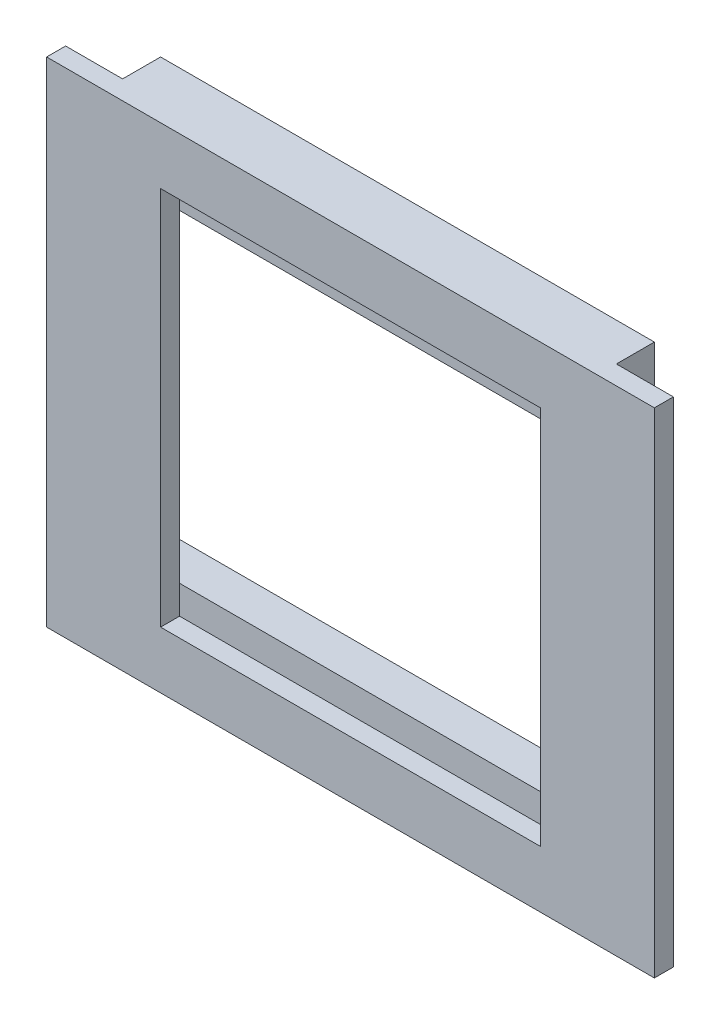
SolidWorks part; units mm, degrees
ref_plane "Спереди" through (0, 0, 0) normal (0, 0, 1) x (1, 0, 0)
ref_plane "Сверху" through (0, 0, 0) normal (0, 1, 0) x (1, 0, 0)
ref_plane "Справа" through (0, 0, 0) normal (1, 0, 0) x (0, 0, -1)
sketch "Sketch1" plane through (0, 0, 0) normal (0, 0, 1) x (1, 0, 0)
  line L1 (-74.5188, 51.1297) -> (55.4812, 51.1297)
  line L2 (-74.5188, 51.1297) -> (-74.5188, -78.8703)
  line L3 (-74.5188, -78.8703) -> (55.4812, -78.8703)
  line L4 (55.4812, 51.1297) -> (55.4812, -78.8703)
  dimension "D1" = 130
  dimension "D2" = 130
extrude "Boss-Extrude1" add sketch "Sketch1" along normal blind 15
sketch "Sketch2" plane through (0, 0, 15) normal (0, 0, 1) x (1, 0, 0)
  line L0 (-74.5188, -78.8703) -> (55.4812, -78.8703) construction
  line L1 (55.4812, 51.1297) -> (70.4812, 51.1297)
  line L2 (55.4812, 51.1297) -> (55.4812, -78.8703)
  line L3 (55.4812, -78.8703) -> (70.4812, -78.8703)
  line L4 (70.4812, 51.1297) -> (70.4812, -78.8703)
  line L5 (-9.5188, 51.1297) -> (-9.5188, -78.8703) construction
  line L6 (55.4812, 51.1297) -> (-74.5188, 51.1297) construction
  line L7 (-74.5188, -78.8703) -> (-89.5188, -78.8703)
  line L8 (-89.5188, 51.1297) -> (-89.5188, -78.8703)
  line L9 (-74.5188, 51.1297) -> (-89.5188, 51.1297)
  line L10 (-74.5188, 51.1297) -> (-74.5188, -78.8703)
  dimension "D1" = 15
extrude "Boss-Extrude2" add sketch "Sketch2" against normal blind 5
sketch "Sketch3" plane through (0, 0, 15) normal (0, 0, 1) x (1, 0, 0)
  line L0 (-89.5188, 51.1297) -> (70.4812, -78.8703)
  line L1 (70.4812, 51.1297) -> (-89.5188, -78.8703)
  line L3 (-59.5188, -63.8703) -> (40.4812, -63.8703)
  line L4 (-59.5188, -63.8703) -> (-59.5188, 36.1297)
  line L5 (-59.5188, 36.1297) -> (40.4812, 36.1297)
  line L6 (40.4812, -63.8703) -> (40.4812, 36.1297)
  line L7 (-59.5188, -63.8703) -> (40.4812, 36.1297) construction
  line L8 (-59.5188, 36.1297) -> (40.4812, -63.8703) construction
  point P6 (-9.5188, -13.8703)
  dimension "D1" = 100
  dimension "D2" = 100
extrude "Cut-Extrude2" cut sketch "Sketch3" against normal blind 5 contours L4 L1 L0 | L1 L6 L5 L4 L0 | L3 L6 L0 L1 L4 | L0 L6 L1
sketch "Sketch5" plane through (0, 0, 10) normal (0, 0, 1) x (1, 0, 0)
  line L0 (-59.5188, -63.8703) -> (40.4812, 36.1297)
  line L1 (-59.5188, -63.8703) -> (40.4812, -63.8703) construction
  line L2 (-59.5188, -63.8703) -> (-59.5188, 36.1297) construction
  line L3 (40.4812, -63.8703) -> (-59.5188, 36.1297)
  line L5 (-47.5188, 28.6297) -> (28.4812, 28.6297)
  line L6 (-47.5188, 28.6297) -> (-47.5188, -56.3703)
  line L7 (-47.5188, -56.3703) -> (28.4812, -56.3703)
  line L8 (28.4812, 28.6297) -> (28.4812, -56.3703)
  line L9 (-47.5188, 28.6297) -> (28.4812, -56.3703) construction
  line L10 (-47.5188, -56.3703) -> (28.4812, 28.6297) construction
  point P12 (-9.5188, -13.8703)
  dimension "D1" = 76
  dimension "D2" = 85
extrude "Cut-Extrude3" cut sketch "Sketch5" against normal through all contours L3 L6 L0 | L8 L5 L6 L3 L0 | L8 L0 L3 | L8 L3 L0 L6 L7
sketch "Sketch8" plane through (0, 0, 0) normal (0, 0, -1) x (-1, 0, 0)
  line L0 (74.5188, 51.1297) -> (74.5188, -78.8703) construction
  line L1 (47.5188, 28.6297) -> (74.5188, 28.6297)
  line L2 (47.5188, 28.6297) -> (47.5188, -56.3703)
  line L3 (47.5188, -56.3703) -> (74.5188, -56.3703)
  line L4 (74.5188, 28.6297) -> (74.5188, -56.3703)
  line L6 (47.5188, -56.3703) -> (-28.4812, -56.3703) construction
  line L7 (9.5188, 51.1297) -> (9.5188, -78.8703) construction
  line L8 (-55.4812, 51.1297) -> (74.5188, 51.1297) construction
  line L9 (74.5188, -78.8703) -> (-55.4812, -78.8703) construction
  line L10 (-28.4812, -56.3703) -> (-55.4812, -56.3703)
  line L11 (-55.4812, 28.6297) -> (-55.4812, -56.3703)
  line L12 (-28.4812, 28.6297) -> (-55.4812, 28.6297)
  line L13 (-28.4812, 28.6297) -> (-28.4812, -56.3703)
extrude "Cut-Extrude5" cut sketch "Sketch8" against normal up to surface (10 mm away) up to face at (62.9812, -13.8703, 10)
